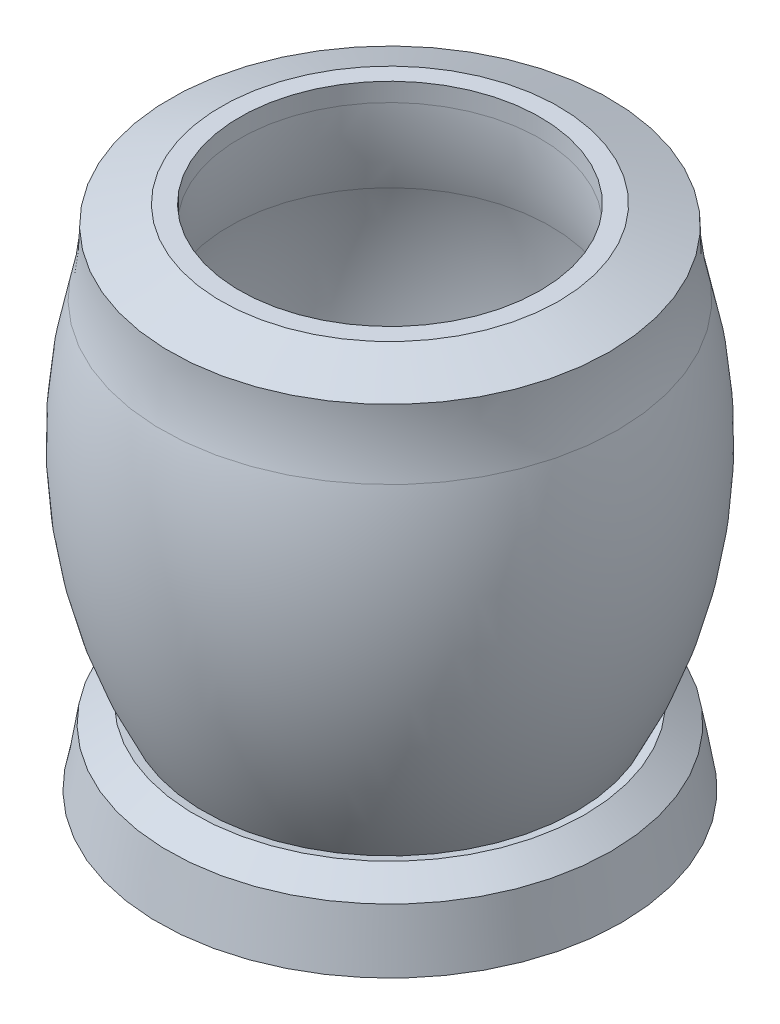
SolidWorks part; units mm, degrees
material "Rubber"
ref_plane "Front Plane" through (0, 0, 0) normal (0, 0, 1) x (1, 0, 0)
ref_plane "Top Plane" through (0, 0, 0) normal (0, 1, 0) x (1, 0, 0)
ref_plane "Right Plane" through (0, 0, 0) normal (1, 0, 0) x (0, 0, -1)
sketch "Sketch1" plane through (0, 0, 0) normal (0, 0, 1) x (1, 0, 0)
  line L0 (0, 0) -> (0, 27.0002) construction
  line L1 (-3.937, 6.8807) -> (-3.937, 0)
  line L2 (-3.937, 0) -> (-12.319, 0)
  line L3 (-12.319, 0) -> (-11.7839, 3.0345)
  line L4 (-11.7839, 3.0345) -> (-10.3783, 4.0188)
  line L5 (-10.3783, 4.0188) -> (-9.9145, 3.937)
  line L6 (-11.6895, 26.0159) -> (-8.9852, 27.0002)
  line L7 (-8.9852, 27.0002) -> (-8.001, 27.0002)
  line L8 (-8.001, 27.0002) -> (-8.001, 26.0159)
  line L9 (-7.5346, 7.5151) -> (-3.937, 6.8807)
  line L10 (-11.6895, 26.0159) -> (-11.6895, 27.0002) construction
  line L11 (-11.6895, 27.0002) -> (-8.9852, 27.0002) construction
  line L12 (-10.3783, 4.0188) -> (-9.9579, 4.0188) construction
  arc A1 (-12.1227, 22.6235) -> (-11.6895, 26.0159) centre (-25.1896, 26.0159) ccw
  arc A2 (-8.001, 26.0159) -> (-8.5526, 21.6966) centre (-25.1896, 26.0159) cw
  arc A3 (-8.5526, 21.6966) -> (-7.5346, 7.5151) centre (12.954, 16.113) ccw
  arc A4 (-12.1227, 22.6235) -> (-9.9145, 3.937) centre (12.954, 16.113) ccw
  dimension "D6" = 13.5001
  dimension "D8" = 25.908
  dimension "D2" = 80
  dimension "D4" = 0.9842
  dimension "D7" = 0.9842
  dimension "D5" = 20
  dimension "D1" = 3.937
  dimension "D9" = 10
  dimension "D10" = 3.937
  dimension "D3" = 35
revolve "Revolve1" add sketch "Sketch1" angle 360 about L0
equation "\"D1@Sketch1\" = \"E@Sketch1\" * 1 / 2"
equation "\"D4@Sketch1\" = \"D1@Sketch1\" * 1 / 4"
equation "\"D7@Sketch1\" = \"D4@Sketch1\""
equation "\"D6@Sketch1\" = \"B@Sketch1\" / 2"
equation "\"D8@Sketch1\" = \"A@Sketch1\""
equation "\"D10@Sketch1\" = \"D1@Sketch1\""
